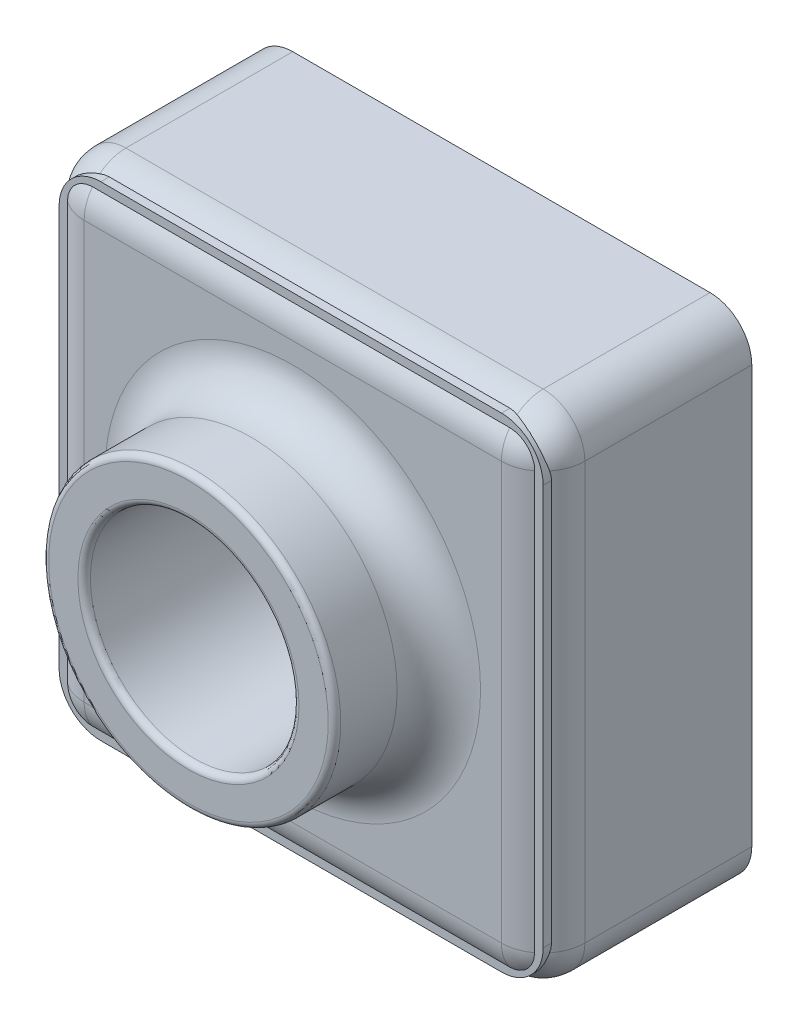
SolidWorks part; units mm, degrees
material "Chrome Stainless Steel"
ref_plane "Front Plane" through (0, 0, 0) normal (0, 0, 1) x (1, 0, 0)
ref_plane "Top Plane" through (0, 0, 0) normal (0, 1, 0) x (1, 0, 0)
ref_plane "Right Plane" through (0, 0, 0) normal (1, 0, 0) x (0, 0, -1)
sketch "Sketch2" plane through (0, 0, 0) normal (0, 0, 1) x (1, 0, 0)
  line L1 (-45.8313, 47.5663) -> (74.1687, 47.5663)
  line L2 (-45.8313, 47.5663) -> (-45.8313, -72.4337)
  line L3 (-45.8313, -72.4337) -> (74.1687, -72.4337)
  line L4 (74.1687, 47.5663) -> (74.1687, -72.4337)
  dimension "D1" = 120
  dimension "D2" = 120
extrude "Boss-Extrude1" add sketch "Sketch2" along normal blind 50
sketch "Sketch3" plane through (0, 0, 50) normal (0, 0, 1) x (1, 0, 0)
  circle A0 centre (14.1687, -12.4337) radius 35
  dimension "D1" = 70
extrude "Boss-Extrude2" add sketch "Sketch3" along normal blind 25
sketch "Sketch5" plane through (0, 0, 75) normal (0, 0, 1) x (1, 0, 0)
  circle A0 centre (14.1687, -12.4337) radius 25
  circle A1 centre (14.1687, -12.4337) radius 35 construction
  dimension "D1" = 10
extrude "Cut-Extrude3" cut sketch "Sketch5" against normal through all contours A0
fillet "Fillet2" radius 1.5 2 edges at (49.1687, -12.4337, 75) (39.1687, -12.4337, 75)
shell "Shell1" thickness 2
fillet "Fillet6" radius 10 13 edges at (14.1687, 47.5663, 50) (74.1687, -12.4337, 50) (14.1687, -72.4337, 50) (-45.8313, -12.4337, 50) (49.1687, -12.4337, 50) (74.1687, 47.5663, 25) (-45.8313, 47.5663, 25) (-45.8313, -72.4337, 25) (74.1687, -72.4337, 25) (-43.8313, -70.4337, 24) (72.1687, -70.4337, 24) (72.1687, 45.5663, 24) (-43.8313, 45.5663, 24)
